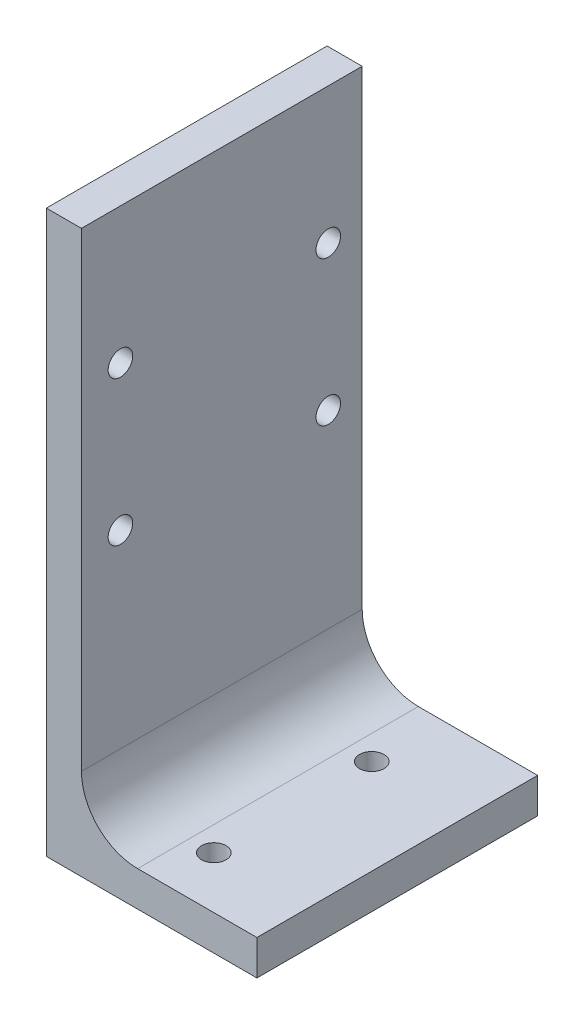
SolidWorks part; units mm, degrees
ref_plane "Plano frontal" through (0, 0, 0) normal (0, 0, 1) x (1, 0, 0)
ref_plane "Plano superior" through (0, 0, 0) normal (0, 1, 0) x (1, 0, 0)
ref_plane "Plano direito" through (0, 0, 0) normal (1, 0, 0) x (0, 0, -1)
sketch "Esboço1" plane through (0, 0, 0) normal (0, 0, 1) x (1, 0, 0)
  line L0 (-30, 40.0262) -> (-30, -39.9738)
  line L1 (-30, -39.9738) -> (0, -39.9738)
  line L2 (0, -39.9738) -> (0, -34.9738)
  line L3 (0, -34.9738) -> (-25, -34.9738)
  line L4 (-25, -34.9738) -> (-25, 40.0262)
  line L5 (-25, 40.0262) -> (-30, 40.0262)
  dimension "D1" = 80
  dimension "D3" = 5
  dimension "D4" = 30
extrude "Ressalto-extrusão1" add sketch "Esboço1" along normal blind 40 contours L4 L5 L0 L1 L2 L3
hole_wizard "Broca de rosquear para helicoide M31" positions "Esboço2" profile "Esboço3" hole size "M3x0.5" standard "Ansi Metric"
sketch "Esboço2" plane through (0, -34.9738, 0) normal (0, 1, 0) x (1, 0, 0)
  point P0 (-13.529, -32.6129)
  point P2 (-13.529, -10.1108)
sketch "Esboço3" plane through (-13.529, -34.9738, 32.6129) normal (1, 0, 0) x (0, 0, 1)
  line L0 (0, 0) -> (0, 11.0515)
  line L1 (0, 11.0515) -> (1.75, 10)
  line L2 (1.75, 10) -> (1.75, 0)
  line L5 (1.75, 0) -> (0, 0)
  line L10 (0, 11.0515) -> (-1.75, 10) construction
  line L11 (0, -6.35) -> (0, 107.95) construction
  dimension "Hole Dia." = 3.5
  dimension "Hole Depth" = 10
  dimension "Drill Angle" = 118
hole_wizard "Broca de rosquear para helicoide M32" positions "Esboço4" profile "Esboço5" hole size "M3x0.5" standard "Ansi Metric"
sketch "Esboço4" plane through (-30, 0, 0) normal (-1, 0, 0) x (0, 0, 1)
  point P0 (4.832, 20.6351)
  point P2 (34.4439, 20.6351)
  point P4 (34.4439, 0)
  point P6 (4.832, 0)
sketch "Esboço5" plane through (-30, 20.6351, 4.832) normal (0, 1, 0) x (0, 0, 1)
  line L0 (0, 0) -> (0, 11.0515)
  line L1 (0, 11.0515) -> (1.75, 10)
  line L2 (1.75, 10) -> (1.75, 0)
  line L5 (1.75, 0) -> (0, 0)
  line L10 (0, 11.0515) -> (-1.75, 10) construction
  line L11 (0, -6.35) -> (0, 107.95) construction
  dimension "Hole Dia." = 3.5
  dimension "Hole Depth" = 10
  dimension "Drill Angle" = 118
fillet "Filete1" radius 8 1 edges at (-25, -34.9738, 20)
